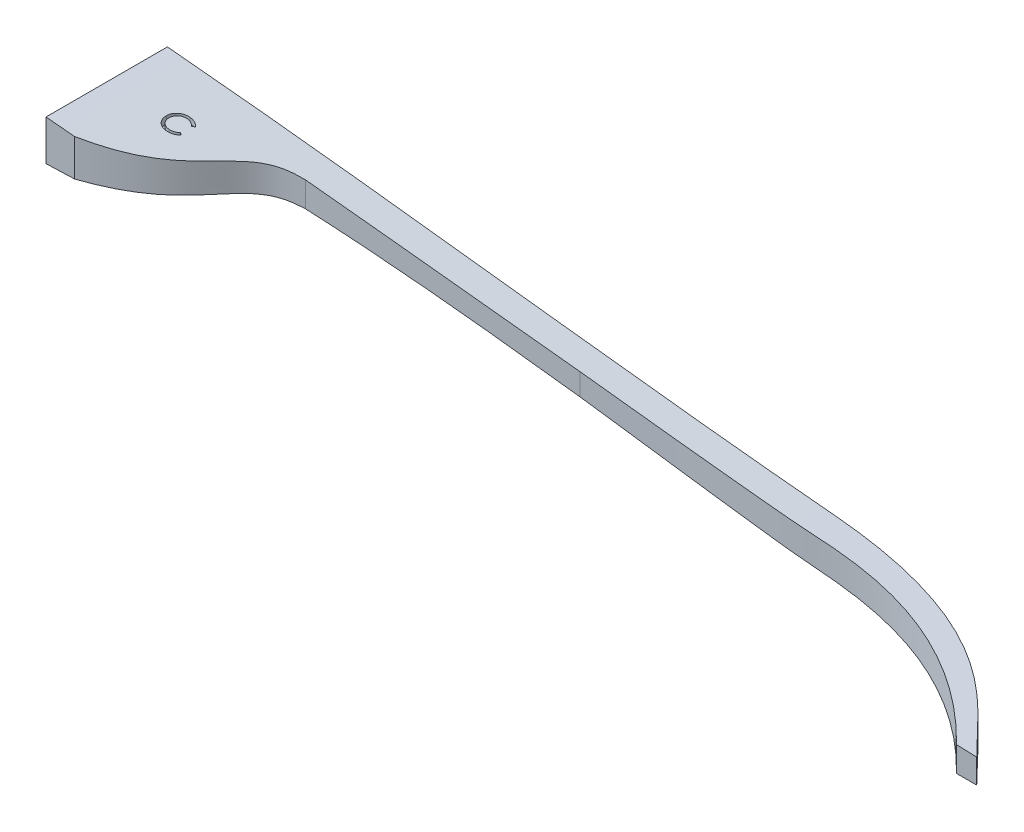
SolidWorks part; units mm, degrees
ref_plane "Front Plane" through (0, 0, 0) normal (0, 0, 1) x (1, 0, 0)
ref_plane "Top Plane" through (0, 0, 0) normal (0, 1, 0) x (1, 0, 0)
ref_plane "Right Plane" through (0, 0, 0) normal (1, 0, 0) x (0, 0, -1)
sketch "Sketch1" plane through (0, 0, 0) normal (0, 1, 0) x (1, 0, 0)
  line L1 (0, 0) -> (146.05, 0)
  line L2 (0, 0) -> (0, 19.05)
  line L3 (0, 19.05) -> (146.05, 19.05)
  line L4 (146.05, 0) -> (146.05, 19.05)
  dimension "D1" = 146.05
  dimension "D2" = 19.05
extrude "Boss-Extrude1" add sketch "Sketch1" along normal blind 17.78
sketch "Sketch3" plane through (0, 0, -19.05) normal (0, 0, -1) x (-1, 0, 0)
  line L0 (0, 17.78) -> (0, 0) construction
  line L1 (-146.05, 17.78) -> (-146.05, 0) construction
  spline S0 degree 3 poles (0, 11.43) (-26.7926, 12.6344) (-75.8961, 5.6906) (-124.0253, -0.5126) (-146.05, 0) knots 0 0 0 0 0.551608 1 1 1 1
  spline S1 degree 3 poles (0, 17.78) (-48.673, 13.4128) (-97.1251, 5.3941) (-146.05, 3.81) knots 0 0 0 0 1 1 1 1
  point P6 (-80.6679, 5.4839)
  point P11 (0, 0)
  point P13 (-80.6679, 8.89)
  line M1 (-146.05, 0) -> (0, 0)
  line M2 (0, 0) -> (0, 17.78)
  line M3 (0, 17.78) -> (-146.05, 17.78)
  line M4 (-146.05, 17.78) -> (-146.05, 0)
  dimension "D1" = 6.35
  dimension "D2" = 3.81
  dimension "D3" = 4.445
  dimension "D4" = 3.6908
sketch "Sketch8" plane through (0, 17.78, 0) normal (0, 1, 0) x (1, 0, 0)
  text T0 "<b>C</b>"
  point P1 (0, 0)
  point P2 (0, 0)
  point P3 (9.1742, 9.99)
  point P4 (8.2078, 8.6371)
extrude "Cut-Extrude7" cut sketch "Sketch8" against normal blind 1.905
sketch "Sketch4" plane through (0, 17.78, 0) normal (0, 1, 0) x (1, 0, 0)
  line L0 (146.05, 19.05) -> (0, 19.05) construction
  line L3 (4.4767, 0) -> (142.875, 0)
  line L4 (146.05, 0) -> (146.05, 19.05)
  line L5 (146.05, 19.05) -> (104.3032, 19.05)
  line L6 (0, 0) -> (146.05, 0) construction
  line L7 (146.05, 0) -> (146.05, 19.05) construction
  spline S0 degree 3 poles (4.4767, 0) (17.7258, 4.0431) (17.0053, 14.2049) (37.6932, 14.9861) (95.0665, 14.824) (108.0685, 14.714) (127.2268, 16.0497) (142.875, 0) knots 0 0 0 0 0.256127 0.322877 0.629203 0.700745 1 1 1 1
  spline S1 degree 3 poles (104.3032, 19.05) (131.3235, 19.1838) (139.2243, 6.6595) (146.05, 0) knots 0 0 0 0 1 1 1 1
  spline S2 degree 1 poles (26.2195, 14.4658) (68.9239, 14.8611) knots 0 0 1 1
  point P6 (0, 0)
  point P13 (0, 0)
  point P17 (0, 0)
  point P18 (0, 0)
  point P19 (26.0226, 11.7378)
  point P20 (94.5373, 16.2492)
  point P21 (0, 0)
  point P22 (99.2036, 15.3249)
  point P23 (0, 0)
  point P24 (100.1486, 14.2483)
  point P26 (0, 0)
  point P27 (26.4138, 13.3599)
  point P28 (0, 0)
  point P29 (101.7607, 15.5107)
  point P30 (0, 0)
  point P31 (68.9239, 14.7754)
  line M2 (146.05, 19.05) -> (0, 19.05)
  line M4 (0, 0) -> (146.05, 0)
  dimension "D1" = 3.175
extrude "Cut-Extrude2" cut sketch "Sketch4" against normal blind 19.05 contours S2 S0 M4 | S1 L4 M2
extrude "Cut-Extrude3" cut sketch "Sketch3" against normal through all contours S0 M2 M1 | S1 M3 M4
sketch "Sketch5" plane through (0, 0, 0) normal (-1, 0, 0) x (0, 0, 1)
  line L0 (0, 11.43) -> (-19.05, 11.43) construction
  line L1 (-5.715, 11.43) -> (-12.7, 11.43)
  line L2 (-5.715, 11.43) -> (-5.715, 15.24)
  line L3 (-5.715, 15.24) -> (-12.7, 15.24)
  line L4 (-12.7, 11.43) -> (-12.7, 15.24)
  line L5 (-19.05, 17.78) -> (-19.05, 11.43) construction
  dimension "D1" = 3.81
  dimension "D2" = 6.985
  dimension "D3" = 6.35
extrude "Cut-Extrude4" cut sketch "Sketch5" against normal blind 6.35
